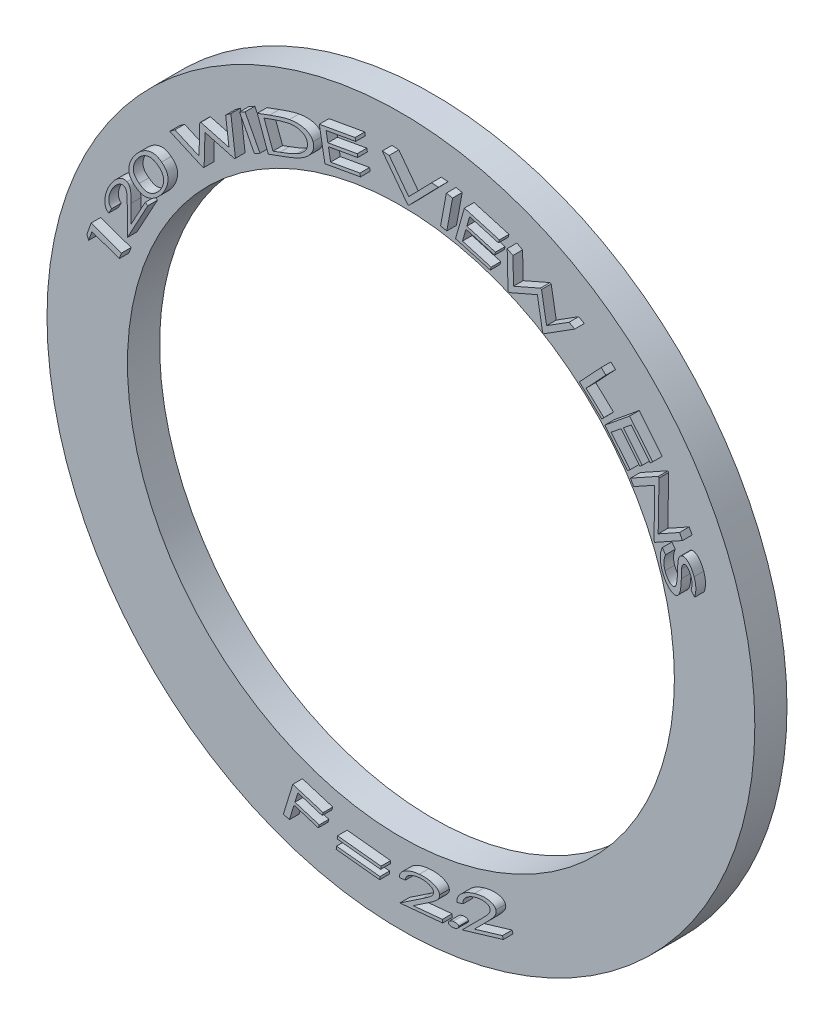
SolidWorks part; units mm, degrees
material "ABS"
ref_plane "Front Plane" through (0, 0, 0) normal (0, 0, 1) x (1, 0, 0)
ref_plane "Top Plane" through (0, 0, 0) normal (0, 1, 0) x (1, 0, 0)
ref_plane "Right Plane" through (0, 0, 0) normal (1, 0, 0) x (0, 0, -1)
sketch "Disc Profile" plane through (0, 0, 0) normal (0, 0, 1) x (1, 0, 0)
  circle A0 centre (0, 0) radius 11
  dimension "D1" = 22
extrude "Disc Extrude" add sketch "Disc Profile" along normal blind 1
sketch "Lens Hole Profile" plane through (0, 0, 1) normal (0, 0, 1) x (1, 0, 0)
  circle A0 centre (0, 0) radius 8.5
  dimension "D1" = 17
extrude "Lens Hole Cut" cut sketch "Lens Hole Profile" against normal through all
sketch "Lens Text 1 Profile" plane through (0, 0, 1) normal (0, 0, 1) x (1, 0, 0)
  line L0 (15.9043, 0) -> (-15.9043, 0) construction
  line L2 (12.8502, 1) -> (-12.8502, 1) construction
  line L3 (0, 0) -> (0, 14.7015) construction
  arc A0 (-9, 0) -> (9, 0) centre (0, 0) ccw construction
  arc A1 (8.9443, 1) -> (-8.9443, 1) centre (0, 0) ccw construction
  text T0 "120 WIDE VIEW LENS" font "Century Gothic" height 1
  point P6 (0, 0)
  point P9 (0, 0)
  point P12 (0, 1)
  dimension "D1" = 18
  dimension "D2" = 1
sketch "Text Guide Profile" plane through (0, 0, 0) normal (0, 0, -1) x (-1, 0, 0)
  circle A0 centre (0, 0) radius 11
sketch "Lens Text 2 Profile" plane through (0, 0, 1) normal (0, 0, 1) x (1, 0, 0)
  line L0 (-11, 0) -> (15.4642, 0) construction
  line L1 (15.9043, 0) -> (-15.9043, 0) construction
  arc A0 (-10, 0) -> (10, 0) centre (0, 0) ccw construction
  circle A1 centre (0, 0) radius 11 construction
  text T0 "F = 2.2" font "Century Gothic" height 1
  dimension "D1" = 10
extrude "Lens Text 1" add sketch "Lens Text 1 Profile" along normal blind 0.3
extrude "Lens Text 2" add sketch "Lens Text 2 Profile" along normal blind 0.3
